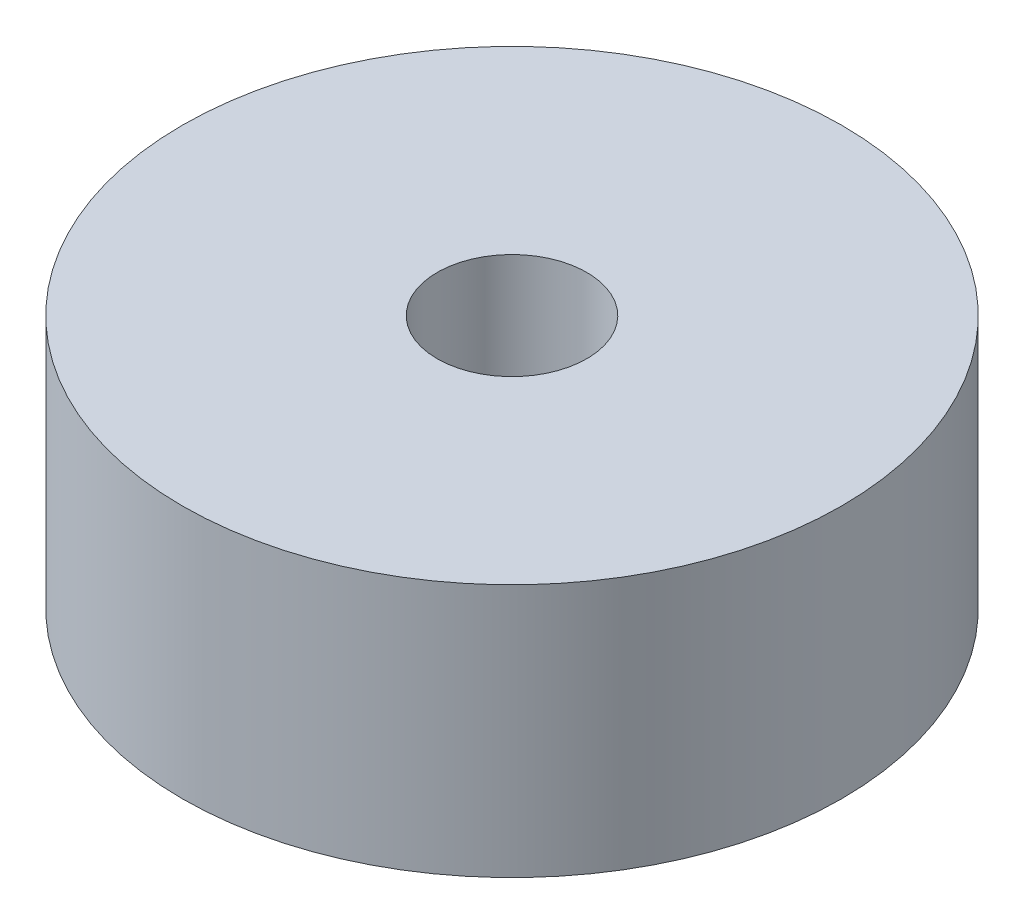
SolidWorks part; units mm, degrees
ref_plane "Front Plane" through (0, 0, 0) normal (0, 0, 1) x (1, 0, 0)
ref_plane "Top Plane" through (0, 0, 0) normal (0, 1, 0) x (1, 0, 0)
ref_plane "Right Plane" through (0, 0, 0) normal (1, 0, 0) x (0, 0, -1)
sketch "Sketch1" plane through (0, 0, 0) normal (0, 1, 0) x (1, 0, 0)
  circle A0 centre (0, 0) radius 6.5
  circle A1 centre (0, 0) radius 1.475
  dimension "D1" = 13
  dimension "D2" = 2.95
extrude "Boss-Extrude1" add sketch "Sketch1" along normal blind 5
